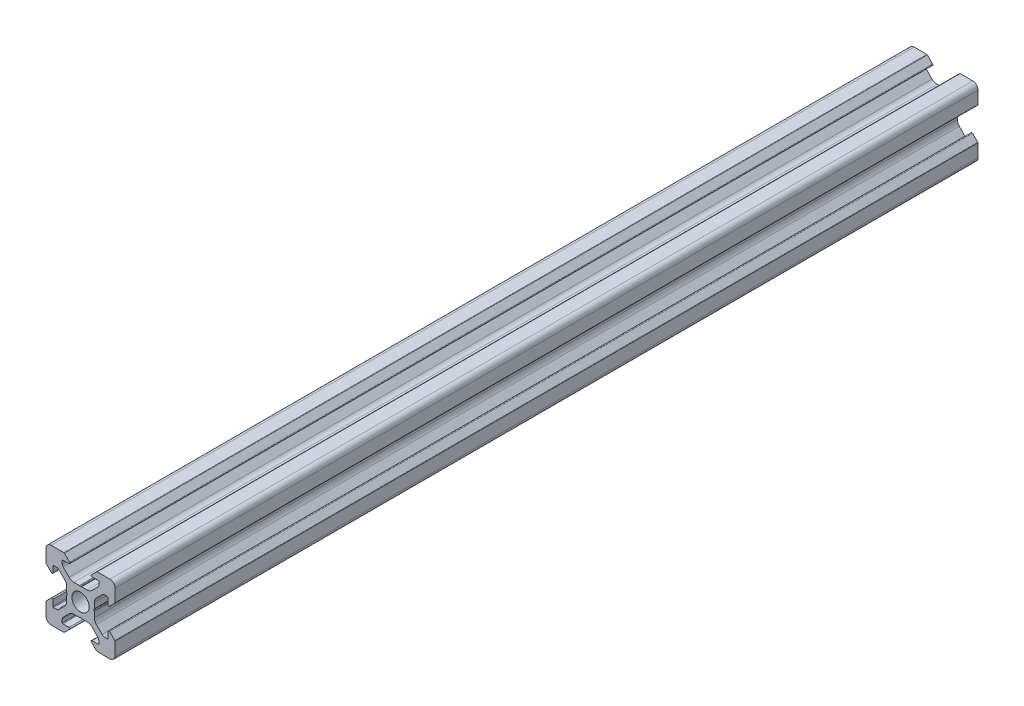
SolidWorks part; units mm, degrees
ref_plane "Спереди" through (0, 0, 0) normal (0, 0, 1) x (1, 0, 0)
ref_plane "Сверху" through (0, 0, 0) normal (0, 1, 0) x (1, 0, 0)
ref_plane "Справа" through (0, 0, 0) normal (1, 0, 0) x (0, 0, -1)
sketch "Сечение" plane through (0, 0, 0) normal (0, 0, 1) x (1, 0, 0)
  line L0 (-4, 1.8988) -> (-4, 0.3377)
  line L1 (-3.9452, 0.1815) -> (-3.8, 0)
  line L2 (-3.8, 0) -> (-3.9452, -0.1815)
  line L3 (-4, -0.3377) -> (-4, -1.8988)
  line L4 (-4.5858, -3.313) -> (-6.2799, -5.0071)
  line L5 (-6.987, -5.3) -> (-7.8, -5.3)
  line L6 (-8, -5.1) -> (-8, -3.33)
  line L7 (-8.4268, -3.1532) -> (-9.9268, -4.6532)
  line L8 (-10, -4.83) -> (-10, -8.5)
  line L9 (-8.5, -10) -> (-4.83, -10)
  line L10 (-4.6532, -9.9268) -> (-3.1532, -8.4268)
  line L11 (-3.33, -8) -> (-5.1, -8)
  line L12 (-5.3, -7.8) -> (-5.3, -6.987)
  line L13 (-5.0071, -6.2799) -> (-3.313, -4.5858)
  line L14 (-1.8988, -4) -> (-0.3377, -4)
  line L15 (-0.1815, -3.9452) -> (0, -3.8)
  line L16 (0, -3.8) -> (0.1815, -3.9452)
  line L17 (0.3377, -4) -> (1.8988, -4)
  line L18 (3.313, -4.5858) -> (5.0071, -6.2799)
  line L19 (5.3, -6.987) -> (5.3, -7.8)
  line L20 (5.1, -8) -> (3.33, -8)
  line L21 (3.1532, -8.4268) -> (4.6532, -9.9268)
  line L22 (4.83, -10) -> (8.5, -10)
  line L23 (10, -8.5) -> (10, -4.83)
  line L24 (9.9268, -4.6532) -> (8.4268, -3.1532)
  line L25 (8, -3.33) -> (8, -5.1)
  line L26 (7.8, -5.3) -> (6.987, -5.3)
  line L27 (6.2799, -5.0071) -> (4.5858, -3.313)
  line L28 (4, -1.8988) -> (4, -0.3377)
  line L29 (3.9452, -0.1815) -> (3.8, 0)
  line L30 (3.8, 0) -> (3.9452, 0.1815)
  line L31 (4, 0.3377) -> (4, 1.8988)
  line L32 (4.5858, 3.313) -> (6.2799, 5.0071)
  line L33 (6.987, 5.3) -> (7.8, 5.3)
  line L34 (8, 5.1) -> (8, 3.33)
  line L35 (8.4268, 3.1532) -> (9.9268, 4.6532)
  line L36 (10, 4.83) -> (10, 8.5)
  line L37 (8.5, 10) -> (4.83, 10)
  line L38 (4.6532, 9.9268) -> (3.1532, 8.4268)
  line L39 (3.33, 8) -> (5.1, 8)
  line L40 (5.3, 7.8) -> (5.3, 6.987)
  line L41 (5.0071, 6.2799) -> (3.313, 4.5858)
  line L42 (1.8988, 4) -> (0.3377, 4)
  line L43 (0.1815, 3.9452) -> (0, 3.8)
  line L44 (0, 3.8) -> (-0.1815, 3.9452)
  line L45 (-0.3377, 4) -> (-1.8988, 4)
  line L46 (-3.313, 4.5858) -> (-5.0071, 6.2799)
  line L47 (-5.3, 6.987) -> (-5.3, 7.8)
  line L48 (-5.1, 8) -> (-3.33, 8)
  line L49 (-3.1532, 8.4268) -> (-4.6532, 9.9268)
  line L50 (-4.83, 10) -> (-8.5, 10)
  line L51 (-10, 8.5) -> (-10, 4.83)
  line L52 (-9.9268, 4.6532) -> (-8.4268, 3.1532)
  line L53 (-8, 3.33) -> (-8, 5.1)
  line L54 (-7.8, 5.3) -> (-6.987, 5.3)
  line L55 (-6.2799, 5.0071) -> (-4.5858, 3.313)
  circle A0 centre (0, 0) radius 2.5
  arc A1 (-4, 0.3377) -> (-3.9452, 0.1815) centre (-3.75, 0.3377) ccw
  arc A2 (-3.9452, -0.1815) -> (-4, -0.3377) centre (-3.75, -0.3377) ccw
  arc A3 (-4, -1.8988) -> (-4.5858, -3.313) centre (-6, -1.8988) cw
  arc A4 (-6.2799, -5.0071) -> (-6.987, -5.3) centre (-6.987, -4.3) cw
  arc A5 (-7.8, -5.3) -> (-8, -5.1) centre (-7.8, -5.1) cw
  arc A6 (-8, -3.33) -> (-8.4268, -3.1532) centre (-8.25, -3.33) ccw
  arc A7 (-9.9268, -4.6532) -> (-10, -4.83) centre (-9.75, -4.83) ccw
  arc A8 (-10, -8.5) -> (-8.5, -10) centre (-8.5, -8.5) ccw
  arc A9 (-4.83, -10) -> (-4.6532, -9.9268) centre (-4.83, -9.75) ccw
  arc A10 (-3.1532, -8.4268) -> (-3.33, -8) centre (-3.33, -8.25) ccw
  arc A11 (-5.1, -8) -> (-5.3, -7.8) centre (-5.1, -7.8) cw
  arc A12 (-5.3, -6.987) -> (-5.0071, -6.2799) centre (-4.3, -6.987) cw
  arc A13 (-3.313, -4.5858) -> (-1.8988, -4) centre (-1.8988, -6) cw
  arc A14 (-0.3377, -4) -> (-0.1815, -3.9452) centre (-0.3377, -3.75) ccw
  arc A15 (0.1815, -3.9452) -> (0.3377, -4) centre (0.3377, -3.75) ccw
  arc A16 (1.8988, -4) -> (3.313, -4.5858) centre (1.8988, -6) cw
  arc A17 (5.0071, -6.2799) -> (5.3, -6.987) centre (4.3, -6.987) cw
  arc A18 (5.3, -7.8) -> (5.1, -8) centre (5.1, -7.8) cw
  arc A19 (3.33, -8) -> (3.1532, -8.4268) centre (3.33, -8.25) ccw
  arc A20 (4.6532, -9.9268) -> (4.83, -10) centre (4.83, -9.75) ccw
  arc A21 (8.5, -10) -> (10, -8.5) centre (8.5, -8.5) ccw
  arc A22 (10, -4.83) -> (9.9268, -4.6532) centre (9.75, -4.83) ccw
  arc A23 (8.4268, -3.1532) -> (8, -3.33) centre (8.25, -3.33) ccw
  arc A24 (8, -5.1) -> (7.8, -5.3) centre (7.8, -5.1) cw
  arc A25 (6.987, -5.3) -> (6.2799, -5.0071) centre (6.987, -4.3) cw
  arc A26 (4.5858, -3.313) -> (4, -1.8988) centre (6, -1.8988) cw
  arc A27 (4, -0.3377) -> (3.9452, -0.1815) centre (3.75, -0.3377) ccw
  arc A28 (3.9452, 0.1815) -> (4, 0.3377) centre (3.75, 0.3377) ccw
  arc A29 (4, 1.8988) -> (4.5858, 3.313) centre (6, 1.8988) cw
  arc A30 (6.2799, 5.0071) -> (6.987, 5.3) centre (6.987, 4.3) cw
  arc A31 (7.8, 5.3) -> (8, 5.1) centre (7.8, 5.1) cw
  arc A32 (8, 3.33) -> (8.4268, 3.1532) centre (8.25, 3.33) ccw
  arc A33 (9.9268, 4.6532) -> (10, 4.83) centre (9.75, 4.83) ccw
  arc A34 (10, 8.5) -> (8.5, 10) centre (8.5, 8.5) ccw
  arc A35 (4.83, 10) -> (4.6532, 9.9268) centre (4.83, 9.75) ccw
  arc A36 (3.1532, 8.4268) -> (3.33, 8) centre (3.33, 8.25) ccw
  arc A37 (5.1, 8) -> (5.3, 7.8) centre (5.1, 7.8) cw
  arc A38 (5.3, 6.987) -> (5.0071, 6.2799) centre (4.3, 6.987) cw
  arc A39 (3.313, 4.5858) -> (1.8988, 4) centre (1.8988, 6) cw
  arc A40 (0.3377, 4) -> (0.1815, 3.9452) centre (0.3377, 3.75) ccw
  arc A41 (-0.1815, 3.9452) -> (-0.3377, 4) centre (-0.3377, 3.75) ccw
  arc A42 (-1.8988, 4) -> (-3.313, 4.5858) centre (-1.8988, 6) cw
  arc A43 (-5.0071, 6.2799) -> (-5.3, 6.987) centre (-4.3, 6.987) cw
  arc A44 (-5.3, 7.8) -> (-5.1, 8) centre (-5.1, 7.8) cw
  arc A45 (-3.33, 8) -> (-3.1532, 8.4268) centre (-3.33, 8.25) ccw
  arc A46 (-4.6532, 9.9268) -> (-4.83, 10) centre (-4.83, 9.75) ccw
  arc A47 (-8.5, 10) -> (-10, 8.5) centre (-8.5, 8.5) ccw
  arc A48 (-10, 4.83) -> (-9.9268, 4.6532) centre (-9.75, 4.83) ccw
  arc A49 (-8.4268, 3.1532) -> (-8, 3.33) centre (-8.25, 3.33) ccw
  arc A50 (-8, 5.1) -> (-7.8, 5.3) centre (-7.8, 5.1) cw
  arc A51 (-6.987, 5.3) -> (-6.2799, 5.0071) centre (-6.987, 4.3) cw
  arc A52 (-4.5858, 3.313) -> (-4, 1.8988) centre (-6, 1.8988) cw
extrude "Длина" add sketch "Сечение" against normal blind 250
